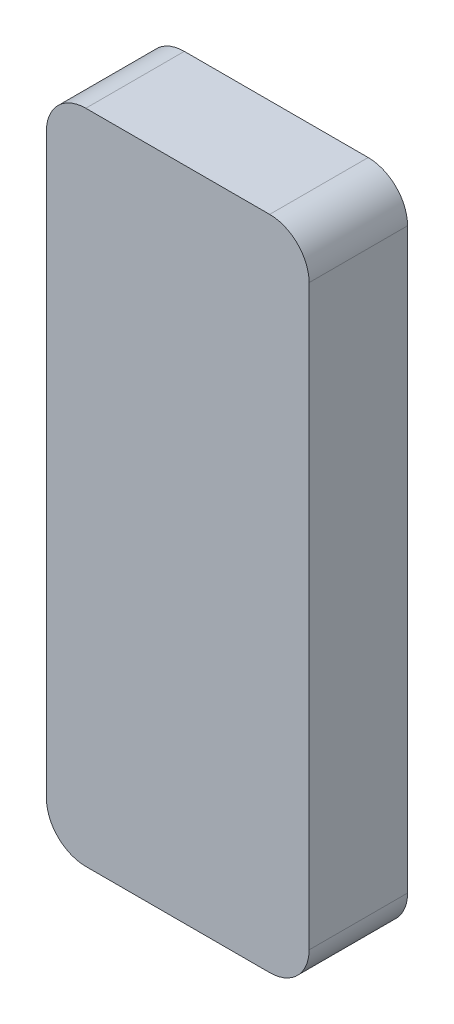
SolidWorks part; units mm, degrees
ref_plane "Front Plane" through (0, 0, 0) normal (0, 0, 1) x (1, 0, 0)
ref_plane "Top Plane" through (0, 0, 0) normal (0, 1, 0) x (1, 0, 0)
ref_plane "Right Plane" through (0, 0, 0) normal (1, 0, 0) x (0, 0, -1)
sketch "Sketch1" plane through (0, 0, 0) normal (0, 0, 1) x (1, 0, 0)
  line L1 (6, 0) -> (34, 0)
  line L2 (0, 6) -> (0, 94)
  line L3 (6, 100) -> (34, 100)
  line L4 (40, 6) -> (40, 94)
  arc A0 (6, 0) -> (0, 6) centre (6, 6) cw
  arc A1 (34, 0) -> (40, 6) centre (34, 6) ccw
  arc A2 (34, 100) -> (40, 94) centre (34, 94) cw
  arc A3 (0, 94) -> (6, 100) centre (6, 94) cw
  point P7 (0, 0)
  point P12 (40, 100)
  point P15 (0, 100)
  dimension "D3" = 6
  dimension "D1" = 100
  dimension "D2" = 40
extrude "Boss-Extrude1" add sketch "Sketch1" along normal blind 15
